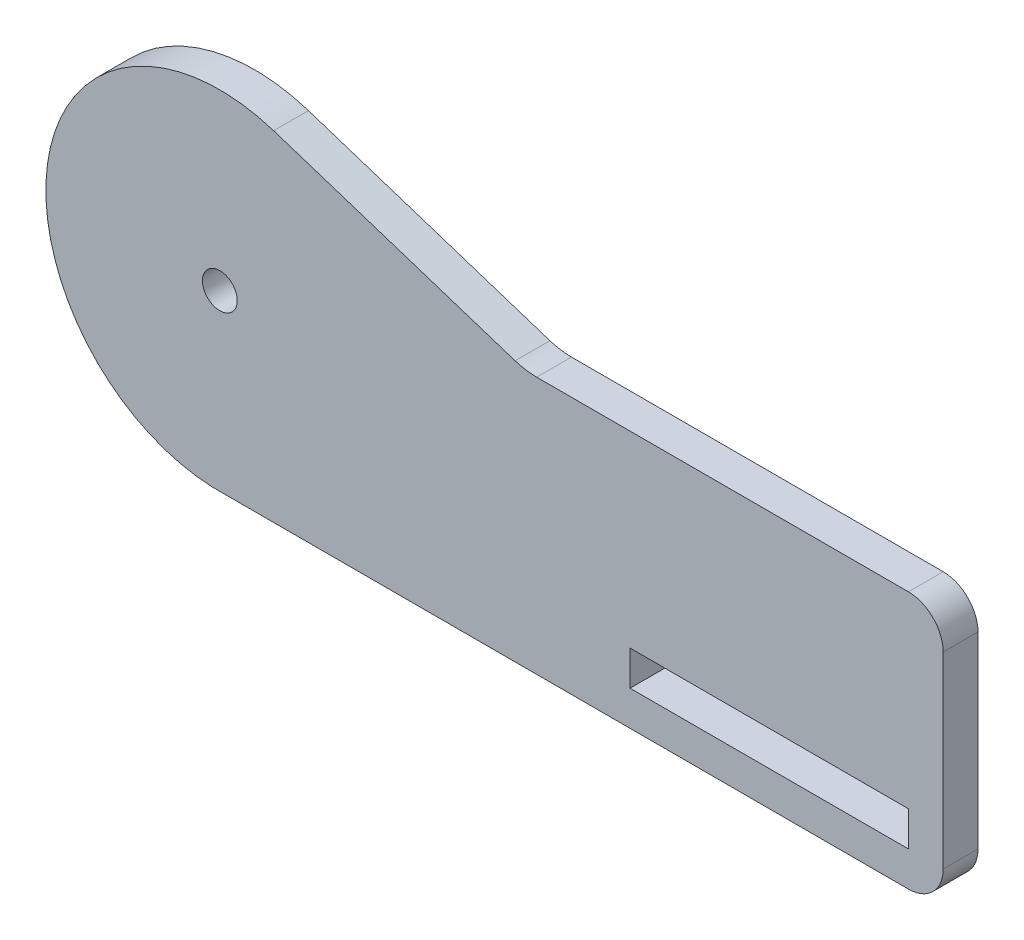
SolidWorks part; units mm, degrees
ref_plane "Alzado" through (0, 0, 0) normal (0, 0, 1) x (1, 0, 0)
ref_plane "Planta" through (0, 0, 0) normal (0, 1, 0) x (1, 0, 0)
ref_plane "Vista lateral" through (0, 0, 0) normal (1, 0, 0) x (0, 0, -1)
sketch "Croquis1" plane through (0, 0, 0) normal (0, 0, 1) x (1, 0, 0)
  line L0 (0, 0) -> (126.9869, 0) construction
  line L1 (78.9415, 12) -> (18.9415, 12)
  line L2 (78.9415, -25) -> (78.9415, 0)
  line L3 (18.9415, 12) -> (-17.2692, 23.7747)
  line L4 (78.9415, 0) -> (78.9415, 12)
  line L5 (-26.0585, -24.9776) -> (78.9415, -25)
  arc A1 (-17.2692, 23.7747) -> (-26.0585, -24.9776) centre (-25, 0) ccw
  dimension "D3" = 25
  dimension "D1" = 105
  dimension "D2" = 25
  dimension "D4" = 60
  dimension "D5" = 12
extrude "Extruir1" add sketch "Croquis1" along normal mid plane 5
fillet "Redondeo1" radius 10 1 edges at (18.9415, 12, 0)
sketch "Croquis2" plane through (0, 0, 2.5) normal (0, 0, 1) x (1, 0, 0)
  circle A2 centre (-25, 0) radius 2.5
  dimension "D1" = 5
extrude "Extruir2" cut sketch "Croquis2" against normal blind 10
fillet "Redondeo2" radius 5 2 edges at (78.9415, -25, 0) (78.9415, 12, 0)
sketch "Croquis4" plane through (0, 0, 2.5) normal (0, 0, 1) x (1, 0, 0)
  line L0 (33.9415, -19.9989) -> (33.9415, -14.9989)
  line L1 (73.9415, -19.9989) -> (33.9415, -19.9989)
  line L2 (53.9415, -19.9989) -> (53.9415, -1.0279) construction
  line L3 (73.9415, -19.9989) -> (73.9415, -14.9989)
  line L4 (33.9415, -14.9989) -> (73.9415, -14.9989)
  line L6 (78.9415, -19.9989) -> (78.9415, 0) construction
  line L7 (-26.0585, -24.9776) -> (73.9404, -24.9989) construction
  dimension "D1" = 5
  dimension "D2" = 40
  dimension "D3" = 5
extrude "Extruir3" cut sketch "Croquis4" against normal blind 10
